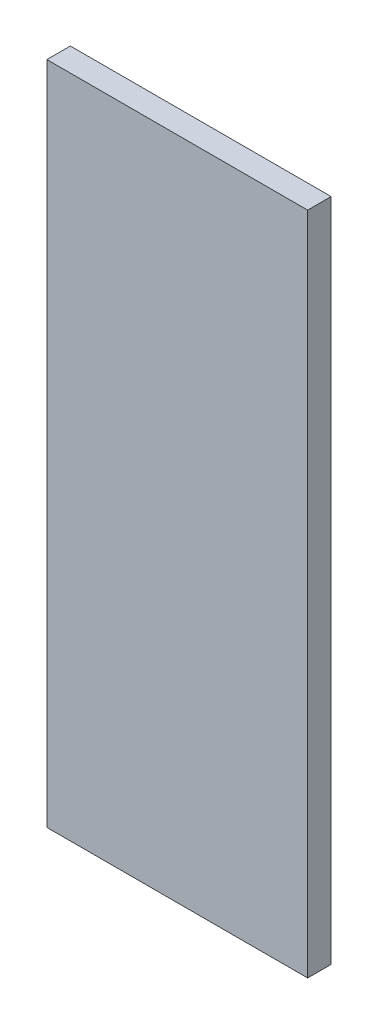
SolidWorks part; units mm, degrees
ref_plane "Front Plane" through (0, 0, 0) normal (0, 0, 1) x (1, 0, 0)
ref_plane "Top Plane" through (0, 0, 0) normal (0, 1, 0) x (1, 0, 0)
ref_plane "Right Plane" through (0, 0, 0) normal (1, 0, 0) x (0, 0, -1)
sketch "Sketch1" plane through (0, 0, 0) normal (0, 0, 1) x (1, 0, 0)
  line L1 (-100, 255) -> (100, 255)
  line L2 (-100, 255) -> (-100, -255)
  line L3 (-100, -255) -> (100, -255)
  line L4 (100, 255) -> (100, -255)
  line L5 (-100, 255) -> (100, -255) construction
  line L6 (-100, -255) -> (100, 255) construction
  point P0 (0, 0)
  dimension "D1" = 510
  dimension "D2" = 200
extrude "Boss-Extrude1" add sketch "Sketch1" along normal blind 18
